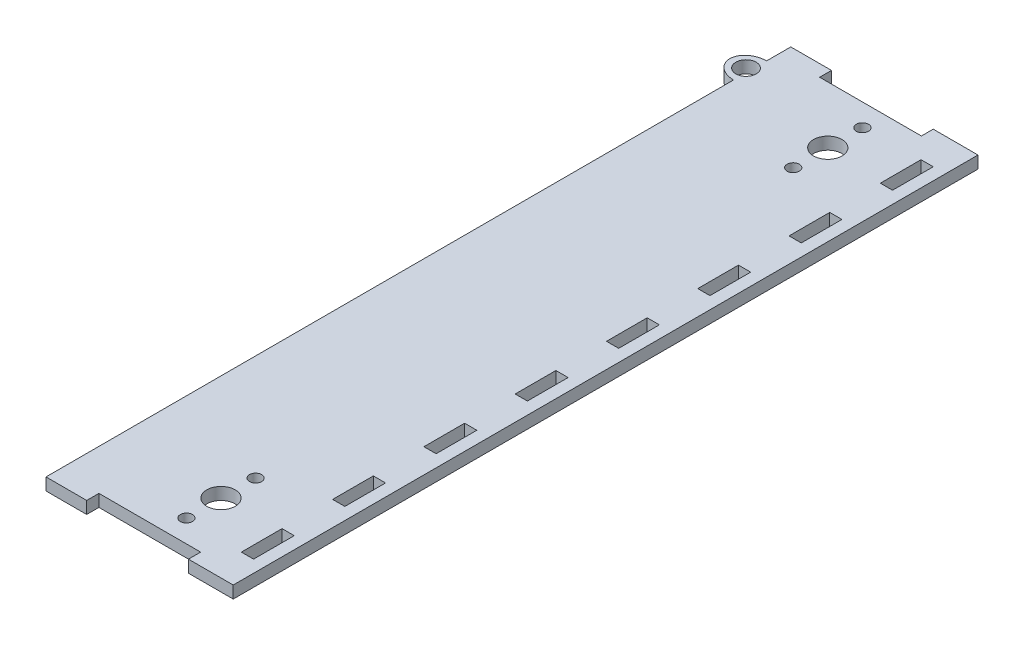
SolidWorks part; units mm, degrees
ref_plane "Front Plane" through (0, 0, 0) normal (0, 0, 1) x (1, 0, 0)
ref_plane "Top Plane" through (0, 0, 0) normal (0, 1, 0) x (1, 0, 0)
ref_plane "Right Plane" through (0, 0, 0) normal (1, 0, 0) x (0, 0, -1)
sketch "Sketch1" plane through (0, 0, 0) normal (0, 1, 0) x (1, 0, 0)
  line L0 (76.2771, 48.8272) -> (76.2771, 38.8272)
  line L1 (36.2771, 79.2558) -> (46.2771, 79.2558)
  line L2 (36.2771, 79.2558) -> (36.2771, 73.3169)
  line L3 (36.2771, -103.7442) -> (46.2771, -103.7442)
  line L4 (82.2771, 79.2558) -> (82.2771, -103.7442)
  line L9 (76.2771, 71.2558) -> (79.2771, 71.2558)
  line L10 (76.2771, 71.2558) -> (76.2771, 61.2558)
  line L11 (76.2771, 61.2558) -> (79.2771, 61.2558)
  line L12 (79.2771, 71.2558) -> (79.2771, 61.2558)
  line L13 (76.2771, 48.8272) -> (79.2771, 48.8272)
  line L14 (79.2771, 48.8272) -> (79.2771, 38.8272)
  line L15 (76.2771, 38.8272) -> (79.2771, 38.8272)
  line L16 (76.2771, 26.3986) -> (76.2771, 16.3986)
  line L17 (76.2771, 26.3986) -> (79.2771, 26.3986)
  line L18 (79.2771, 26.3986) -> (79.2771, 16.3986)
  line L19 (76.2771, 16.3986) -> (79.2771, 16.3986)
  line L20 (76.2771, 3.9701) -> (76.2771, -6.0299)
  line L21 (76.2771, 3.9701) -> (79.2771, 3.9701)
  line L22 (79.2771, 3.9701) -> (79.2771, -6.0299)
  line L23 (76.2771, -6.0299) -> (79.2771, -6.0299)
  line L24 (76.2771, -18.4585) -> (76.2771, -28.4585)
  line L25 (76.2771, -18.4585) -> (79.2771, -18.4585)
  line L26 (79.2771, -18.4585) -> (79.2771, -28.4585)
  line L27 (76.2771, -28.4585) -> (79.2771, -28.4585)
  line L28 (76.2771, -40.8871) -> (76.2771, -50.8871)
  line L29 (76.2771, -40.8871) -> (79.2771, -40.8871)
  line L30 (79.2771, -40.8871) -> (79.2771, -50.8871)
  line L31 (76.2771, -50.8871) -> (79.2771, -50.8871)
  line L32 (76.2771, -63.3156) -> (76.2771, -73.3156)
  line L33 (76.2771, -63.3156) -> (79.2771, -63.3156)
  line L34 (79.2771, -63.3156) -> (79.2771, -73.3156)
  line L35 (76.2771, -73.3156) -> (79.2771, -73.3156)
  line L36 (76.2771, -85.7442) -> (76.2771, -95.7442)
  line L37 (76.2771, -85.7442) -> (79.2771, -85.7442)
  line L38 (79.2771, -85.7442) -> (79.2771, -95.7442)
  line L39 (76.2771, -95.7442) -> (79.2771, -95.7442)
  line L40 (36.2771, 65.1947) -> (36.2771, -103.7442)
  line L42 (46.2771, 79.2558) -> (46.2771, 76.3477)
  line L43 (46.2771, 76.3477) -> (71.2771, 76.3477)
  line L44 (71.2771, 79.2558) -> (71.2771, 76.3477)
  line L46 (71.2771, -103.7442) -> (71.2771, -100.7442)
  line L47 (71.2771, -100.7442) -> (46.2771, -100.7442)
  line L48 (46.2771, -103.7442) -> (46.2771, -100.7442)
  line L49 (71.2771, 79.2558) -> (82.2771, 79.2558)
  line L50 (71.2771, -103.7442) -> (82.2771, -103.7442)
  circle A1 centre (35.2771, 69.2558) radius 2.5
  circle A2 centre (62.2771, 62.3477) radius 3.5
  circle A3 centre (62.2771, 70.8477) radius 1.5
  circle A4 centre (62.2771, 53.8477) radius 1.5
  circle A5 centre (62.2771, -86.7442) radius 3.5
  circle A6 centre (62.2771, -78.2442) radius 1.5
  circle A7 centre (62.2771, -95.2442) radius 1.5
  ellipse E0 centre (36.2771, 69.2558) end of major axis (31.2891, 69.2558) minor radius 4.0611 (36.2771, 73.3169) -> (36.2771, 65.1947) ccw
  point P67 (62.4099, -89.6832)
  dimension "D9" = 1
  dimension "D11" = 5
  dimension "D18" = 7
  dimension "D21" = 3
  dimension "D1" = 183
  dimension "D2" = 46
  dimension "D3" = 3
  dimension "D4" = 8
  dimension "D5" = 3
  dimension "D6" = 10
  dimension "D8" = 8
  dimension "D10" = 10
  dimension "D12" = 5
  dimension "D13" = 25
  dimension "D14" = 2.9081
  dimension "D15" = 3
  dimension "D16" = 14
  dimension "D17" = 14
  dimension "D19" = 14
  dimension "D20" = 8.5
  dimension "D22" = 14
  dimension "D23" = 8.5
  dimension "D24" = 14
  dimension "D25" = 14
  dimension "D26" = 8.5
  dimension "D27" = 8.5
  dimension "D28" = 14
  dimension "D29" = 14
  dimension "D7" = 8
extrude "Boss-Extrude3" add sketch "Sketch1" along normal blind 3
